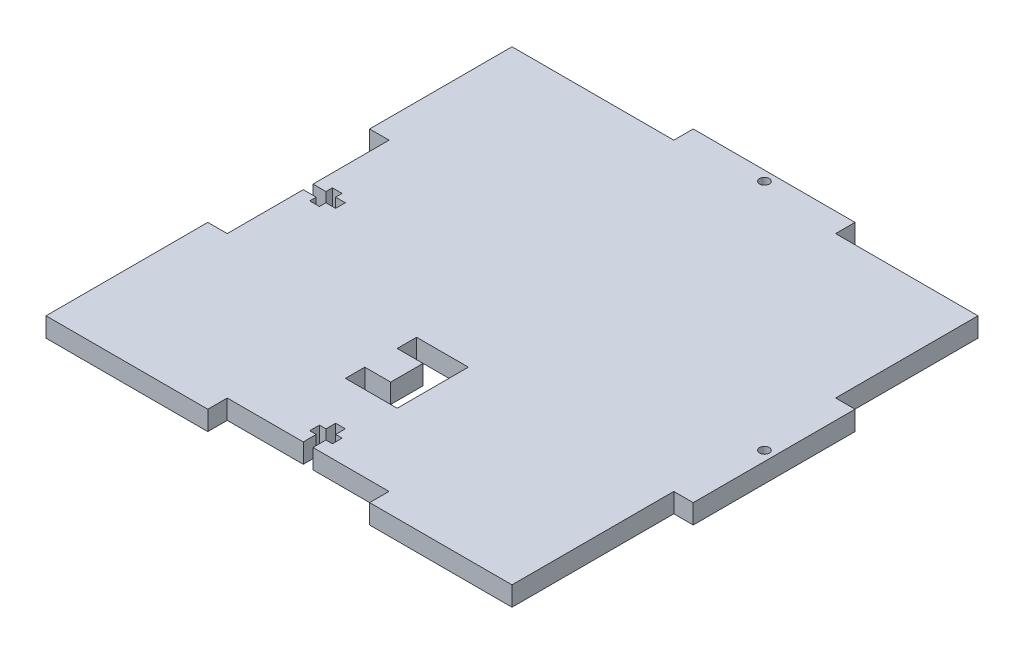
SolidWorks part; units mm, degrees
material "Acrylic (Medium-high impact)"
ref_plane "Front Plane" through (0, 0, 0) normal (0, 0, 1) x (1, 0, 0)
ref_plane "Top Plane" through (0, 0, 0) normal (0, 1, 0) x (1, 0, 0)
ref_plane "Right Plane" through (0, 0, 0) normal (1, 0, 0) x (0, 0, -1)
sketch "Sketch1" plane through (0, 0, 0) normal (0, 1, 0) x (1, 0, 0)
  line L0 (-72, 28) -> (-66, 28)
  line L1 (-72, -72) -> (72, -72)
  line L2 (-72, -72) -> (-72, 72)
  line L3 (-72, 72) -> (72, 72)
  line L4 (72, -72) -> (72, 72)
  line L5 (-72, -72) -> (72, 72) construction
  line L6 (-72, 72) -> (72, -72) construction
  line L7 (-66, 28) -> (-66, -22)
  line L8 (28, -72) -> (28, -66)
  line L9 (-22, 72) -> (-22, 78)
  line L10 (-22, 78) -> (28, 78)
  line L11 (28, 72) -> (28, 78)
  line L12 (72, 28) -> (78, 28)
  line L13 (78, 28) -> (78, -22)
  line L14 (-22, -72) -> (-22, -66)
  line L15 (-22, -66) -> (28, -66)
  line L16 (3, 78) -> (3, -72) construction
  line L17 (-72, 3) -> (78, 3) construction
  line L18 (72, -22) -> (78, -22)
  line L19 (-72, -22) -> (-66, -22)
  line L20 (75, 28) -> (75, -22) construction
  line L21 (4.5, -66) -> (4.5, -62)
  line L22 (4.5, -62) -> (6.5, -62)
  line L23 (6.5, -62) -> (6.5, -59)
  line L24 (6.5, -59) -> (4.5, -59)
  line L25 (4.5, -59) -> (4.5, -56)
  line L26 (4.5, -56) -> (1.5, -56)
  line L27 (1.5, -66) -> (1.5, -62)
  line L28 (1.5, -62) -> (-0.5, -62)
  line L29 (-0.5, -59) -> (1.5, -59)
  line L30 (-0.5, -62) -> (-0.5, -59)
  line L31 (1.5, -59) -> (1.5, -56)
  line L32 (-59, 4.5) -> (-56, 4.5)
  line L33 (-62, 4.5) -> (-62, 6.5)
  line L34 (-59, 6.5) -> (-59, 4.5)
  line L35 (-62, 6.5) -> (-59, 6.5)
  line L36 (-66, 4.5) -> (-62, 4.5)
  line L37 (-66, 1.5) -> (-62, 1.5)
  line L38 (-62, 1.5) -> (-62, -0.5)
  line L39 (-62, -0.5) -> (-59, -0.5)
  line L40 (-59, -0.5) -> (-59, 1.5)
  line L41 (-59, 1.5) -> (-56, 1.5)
  line L42 (-56, 4.5) -> (-56, 1.5)
  line L43 (-1, -20.4849) -> (-9, -20.4849)
  line L48 (-1, -42.4849) -> (7, -42.4849)
  line L49 (-1, -42.4849) -> (-1, -20.4849)
  line L50 (-1, -20.4849) -> (7, -20.4849)
  line L51 (7, -42.4849) -> (7, -20.4849)
  line L52 (-1, -42.4849) -> (7, -20.4849) construction
  line L53 (-1, -20.4849) -> (7, -42.4849) construction
  line L54 (-9, -20.4849) -> (-9, -26.4849)
  line L55 (-9, -26.4849) -> (-1, -26.4849)
  line L57 (-13.4228, -31.4849) -> (19.4228, -31.4849) construction
  line L58 (-9, -36.4849) -> (-1, -36.4849)
  line L59 (-9, -42.4849) -> (-9, -36.4849)
  line L60 (-1, -42.4849) -> (-9, -42.4849)
  circle A0 centre (75, 3) radius 1.5
  circle A1 centre (3, 75) radius 1.5
  point P0 (0, 0)
  point P22 (3, 3)
  point P27 (3, 3)
  point P40 (3, -66)
  point P45 (-66, 3)
  point P49 (3, -56)
  point P61 (3, -31.4849)
  point P72 (3, -31.4849)
  dimension "D4" = 3
  dimension "D1" = 144
  dimension "D2" = 25
  dimension "D3" = 6
  dimension "D5" = 4
  dimension "D6" = 2
  dimension "D7" = 3
  dimension "D8" = 1.5
  dimension "D9" = 22
  dimension "D10" = 8
  dimension "D11" = 6
extrude "Boss-Extrude1" add sketch "Sketch1" along normal blind 6 contours L19 L2 L1 L14 L15 L8 L4 L3 L0 L7 | L3 L11 L10 L9 | L4 L18 L13 L12
